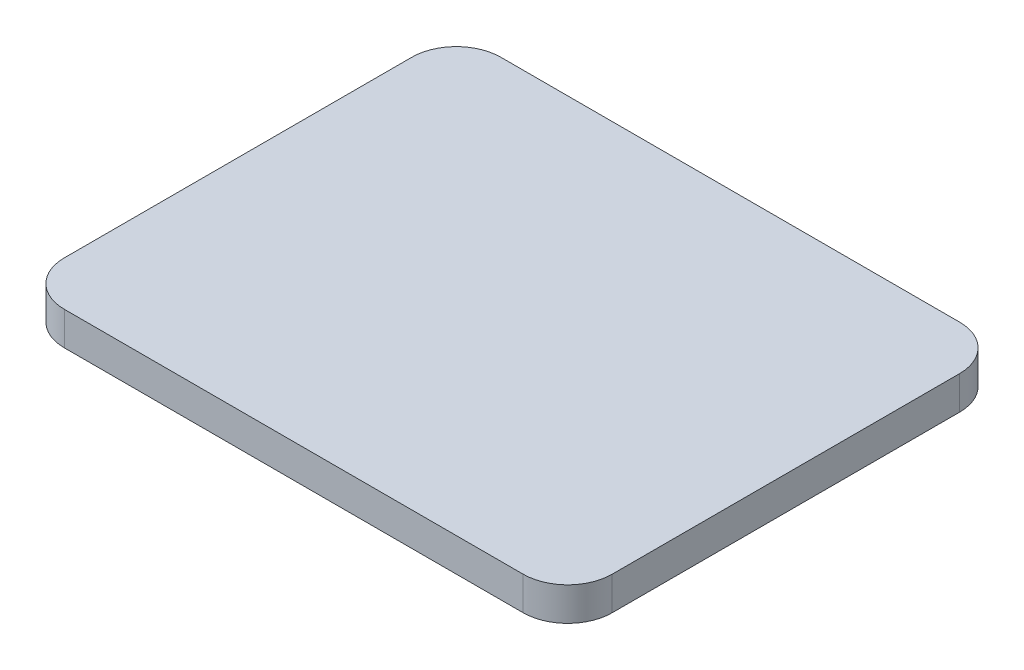
SolidWorks part; units mm, degrees
ref_plane "Front Plane" through (0, 0, 0) normal (0, 0, 1) x (1, 0, 0)
ref_plane "Top Plane" through (0, 0, 0) normal (0, 1, 0) x (1, 0, 0)
ref_plane "Right Plane" through (0, 0, 0) normal (1, 0, 0) x (0, 0, -1)
sketch "Sketch1" plane through (0, 0, 0) normal (0, 1, 0) x (1, 0, 0)
  line L1 (0, 0) -> (62.484, 0)
  line L2 (0, 0) -> (0, -49.784)
  line L3 (0, -49.784) -> (62.484, -49.784)
  line L4 (62.484, 0) -> (62.484, -49.784)
  dimension "D1" = 49.784
  dimension "D2" = 62.484
extrude "Boss-Extrude1" add sketch "Sketch1" along normal blind 3.81 contours L2 L1 L4 L3
sketch "Sketch2" plane through (0, 0, 0) normal (0, -1, 0) x (1, 0, 0)
  line L4 (56.007, 43.307) -> (6.477, 43.307)
  line L5 (6.477, 43.307) -> (6.477, 6.477)
  line L6 (6.477, 6.477) -> (56.007, 6.477)
  line L7 (56.007, 6.477) -> (56.007, 43.307)
  line L8 (58.547, 45.847) -> (3.937, 45.847)
  line L9 (3.937, 45.847) -> (3.937, 3.937)
  line L10 (3.937, 3.937) -> (58.547, 3.937)
  line L11 (58.547, 3.937) -> (58.547, 45.847)
  line L12 (58.547, 45.847) -> (3.937, 45.847)
  line L13 (3.937, 45.847) -> (3.937, 3.937)
  line L14 (3.937, 3.937) -> (58.547, 3.937)
  line L15 (58.547, 3.937) -> (58.547, 45.847)
  dimension "D1" = 3.937
  dimension "D2" = 2.54
extrude "Boss-Extrude3" add sketch "Sketch2" along normal blind 3.81
fillet "Fillet1" radius 5.08 4 edges at (62.484, 1.905, 0) (62.484, 1.905, 49.784) (0, 1.905, 49.784) (0, 1.905, 0)
fillet "Fillet2" radius 5.08 4 edges at (3.937, -1.905, 45.847) (3.937, -1.905, 3.937) (58.547, -1.905, 3.937) (58.547, -1.905, 45.847)
fillet "Fillet3" radius 2.54 4 edges at (6.477, -1.905, 6.477) (56.007, -1.905, 6.477) (56.007, -1.905, 43.307) (6.477, -1.905, 43.307)
